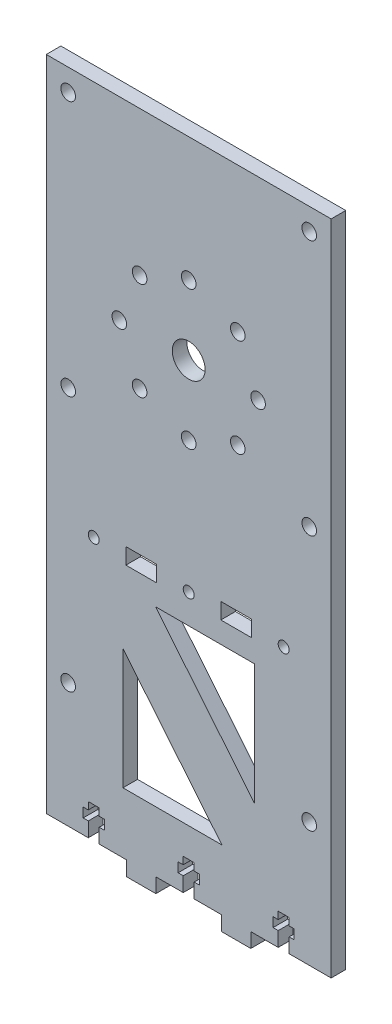
SolidWorks part; units mm, degrees
ref_plane "前视基准面" through (0, 0, 0) normal (0, 0, 1) x (1, 0, 0)
ref_plane "上视基准面" through (0, 0, 0) normal (0, 1, 0) x (1, 0, 0)
ref_plane "右视基准面" through (0, 0, 0) normal (1, 0, 0) x (0, 0, -1)
sketch "草图1" plane through (0, 0, 0) normal (0, 0, 1) x (1, 0, 0)
  line L0 (-4, -20.5) -> (-29, -20.5) construction
  line L7 (-43, 32.5) -> (35, 32.5)
  line L8 (-43, 32.5) -> (-43, -147.5)
  line L9 (-43, -147.5) -> (35, -147.5)
  line L10 (35, 32.5) -> (35, -147.5)
  circle A0 centre (-4, -20.5) radius 4.5
  circle A11 centre (-4, -20.5) radius 19 construction
  circle A12 centre (15, -20.5) radius 2
  circle A26 centre (9.435, -33.935) radius 2
  circle A27 centre (-4, -39.5) radius 2
  circle A28 centre (-17.435, -33.935) radius 2
  circle A29 centre (-23, -20.5) radius 2
  circle A30 centre (-17.435, -7.065) radius 2
  circle A31 centre (-4, -1.5) radius 2
  circle A32 centre (9.435, -7.065) radius 2
  dimension "D1" = 9
  dimension "D2" = 38
  dimension "D6" = 127
  dimension "D7" = 180
  dimension "D8" = 78
  dimension "D9" = 39
extrude "凸台-拉伸1" add sketch "草图1" along normal blind 4
sketch "草图2" plane through (0, 0, 4) normal (0, 0, 1) x (1, 0, 0)
  line L0 (-43, 32.5) -> (-43, -147.5) construction
  line L1 (35, 32.5) -> (-43, 32.5) construction
  line L40 (-30, -75.5) -> (-4, -75.5) construction
  line L41 (-4, -75.5) -> (22, -75.5) construction
  line L42 (-15.7985, 32.5) -> (-15.7985, -147.5) construction
  line L43 (-43, -147.5) -> (35, -147.5) construction
  line L44 (-15.7985, -57.5) -> (-8.8, -57.5) construction
  line L81 (9, -147.5) -> (9, -140.6052) construction
  line L82 (22, -147.5) -> (22, -155.1147) construction
  line L83 (-21.2, -73.3) -> (-12.8, -73.3)
  line L84 (-21.2, -73.3) -> (-21.2, -77.7)
  line L85 (-21.2, -77.7) -> (-12.8, -77.7)
  line L86 (-12.8, -73.3) -> (-12.8, -77.7)
  line L87 (-21.2, -73.3) -> (-12.8, -77.7) construction
  line L88 (-21.2, -77.7) -> (-12.8, -73.3) construction
  line L89 (4.8, -73.3) -> (13.2, -73.3)
  line L90 (4.8, -73.3) -> (4.8, -77.7)
  line L91 (4.8, -77.7) -> (13.2, -77.7)
  line L92 (13.2, -73.3) -> (13.2, -77.7)
  line L93 (4.8, -73.3) -> (13.2, -77.7) construction
  line L94 (4.8, -77.7) -> (13.2, -73.3) construction
  line L95 (-4, -147.5) -> (-4, -151.3851) construction
  line L96 (-31.5, -147.5) -> (-31.5, -143.5)
  line L97 (-31.5, -143.5) -> (-32.9, -143.5)
  line L98 (-32.9, -143.5) -> (-32.9, -140.9)
  line L99 (-32.9, -140.9) -> (-31.5, -140.9)
  line L100 (-31.5, -140.9) -> (-31.5, -138.9)
  line L101 (-28.5, -138.9) -> (-31.5, -138.9)
  line L102 (-28.5, -140.9) -> (-28.5, -138.9)
  line L103 (-27.1, -140.9) -> (-28.5, -140.9)
  line L104 (-27.1, -143.5) -> (-27.1, -140.9)
  line L105 (-28.5, -143.5) -> (-27.1, -143.5)
  line L106 (-28.5, -147.5) -> (-28.5, -143.5)
  line L107 (-31.5, -147.5) -> (-28.5, -147.5)
  line L108 (23.5, -147.5) -> (20.5, -147.5)
  line L109 (20.5, -147.5) -> (20.5, -143.5)
  line L110 (20.5, -143.5) -> (19.1, -143.5)
  line L111 (19.1, -143.5) -> (19.1, -140.9)
  line L112 (19.1, -140.9) -> (20.5, -140.9)
  line L113 (20.5, -140.9) -> (20.5, -138.9)
  line L114 (20.5, -138.9) -> (23.5, -138.9)
  line L115 (23.5, -140.9) -> (23.5, -138.9)
  line L116 (24.9, -140.9) -> (23.5, -140.9)
  line L117 (24.9, -143.5) -> (24.9, -140.9)
  line L118 (23.5, -143.5) -> (24.9, -143.5)
  line L119 (23.5, -147.5) -> (23.5, -143.5)
  line L120 (-5.5, -147.5) -> (-5.5, -143.5)
  line L121 (-5.5, -143.5) -> (-6.9, -143.5)
  line L122 (-6.9, -143.5) -> (-6.9, -140.9)
  line L123 (-6.9, -140.9) -> (-5.5, -140.9)
  line L124 (-5.5, -140.9) -> (-5.5, -138.9)
  line L125 (-2.5, -138.9) -> (-5.5, -138.9)
  line L126 (-2.5, -140.9) -> (-2.5, -138.9)
  line L127 (-1.1, -140.9) -> (-2.5, -140.9)
  line L128 (-1.1, -143.5) -> (-1.1, -140.9)
  line L129 (-2.5, -143.5) -> (-1.1, -143.5)
  line L130 (-2.5, -147.5) -> (-2.5, -143.5)
  line L131 (-5.5, -147.5) -> (-2.5, -147.5)
  circle A0 centre (-4, -75.5) radius 1.5
  circle A1 centre (22, -75.5) radius 1.5
  circle A2 centre (-30, -75.5) radius 1.5
  point P101 (-17, -75.5)
  point P106 (9, -75.5)
  point P112 (-30, -138.9)
  point P113 (22, -138.9)
  point P114 (-4, -138.9)
  dimension "D8" = 72
  dimension "D9" = 26
  dimension "D11" = 3
  dimension "D12" = 3
  dimension "D13" = 3
  dimension "D2" = 39
  dimension "D10" = 26
  dimension "D14" = 4.4
  dimension "D15" = 8.4
extrude "切除-拉伸1" cut sketch "草图2" against normal blind 4
sketch "草图4" plane through (0, -147.5, 0) normal (0, -1, 0) x (1, 0, 0)
  line L0 (-5.5, 2) -> (-2.5, 2)
  line L3 (-2.5, 4) -> (-4, 4)
  line L4 (-2.5, 2) -> (-2.2521, 2) construction
  line L5 (-2.5, 0) -> (-2.5, 4) construction
  circle A0 centre (-4, 2) radius 1.5
sketch "草图6" plane through (0, 0, 4) normal (0, 0, 1) x (1, 0, 0)
  line L0 (-17, -77.7) -> (-17, -134.4477) construction
  line L1 (-21.2, -77.7) -> (-12.8, -77.7) construction
  line L3 (-21, -143.5) -> (-13, -143.5)
  line L4 (-21, -143.5) -> (-21, -151.5)
  line L5 (-21, -151.5) -> (-13, -151.5)
  line L6 (-13, -143.5) -> (-13, -151.5)
  line L7 (-21, -143.5) -> (-13, -151.5) construction
  line L8 (-21, -151.5) -> (-13, -143.5) construction
  line L9 (5, -151.5) -> (13, -151.5)
  line L10 (5, -151.5) -> (5, -143.5)
  line L11 (5, -143.5) -> (13, -143.5)
  line L12 (13, -151.5) -> (13, -143.5)
  line L13 (5, -151.5) -> (13, -143.5) construction
  line L14 (5, -143.5) -> (13, -151.5) construction
  point P8 (9, -147.5)
  point P13 (-17, -147.5)
  dimension "D1" = 26
extrude "凸台-拉伸2" add sketch "草图6" against normal blind 4
sketch "草图7" plane through (0, 0, 0) normal (0, 0, -1) x (-1, 0, 0)
  line L0 (-35, 32.5) -> (43, 32.5) construction
  line L1 (-35, -147.5) -> (-35, 32.5) construction
  line L2 (-22, -75.5) -> (-22, -138.9) construction
  line L3 (-23.5, -138.9) -> (-20.5, -138.9) construction
  line L4 (-22, -138.9) -> (30, -75.5) construction
  line L5 (30, -75.5) -> (-22, -75.5) construction
  line L6 (-14, -83.5) -> (-14, -116.5312)
  line L7 (-14, -116.5312) -> (13.0918, -83.5)
  line L8 (13.0918, -83.5) -> (-14, -83.5)
  line L9 (-22, -138.9) -> (30, -138.9) construction
  line L10 (28.5, -138.9) -> (31.5, -138.9) construction
  line L11 (30, -138.9) -> (30, -75.5) construction
  line L12 (-5.0918, -130.9) -> (22, -97.8688)
  line L13 (22, -130.9) -> (22, -97.8688)
  line L14 (-5.0918, -130.9) -> (22, -130.9)
  circle A0 centre (-29, 26.5) radius 2
  circle A1 centre (-29, -43.5) radius 2
  circle A2 centre (-29, -113.5) radius 2
  circle A3 centre (37, -43.5) radius 2
  circle A4 centre (37, -113.5) radius 2
  circle A5 centre (37, 26.5) radius 2
  dimension "D1" = 6
  dimension "D2" = 6
  dimension "D5" = 8
  dimension "D6" = 8
  dimension "D3" = 3
  dimension "D4" = 2
extrude "切除-拉伸2" cut sketch "草图7" against normal blind 10
